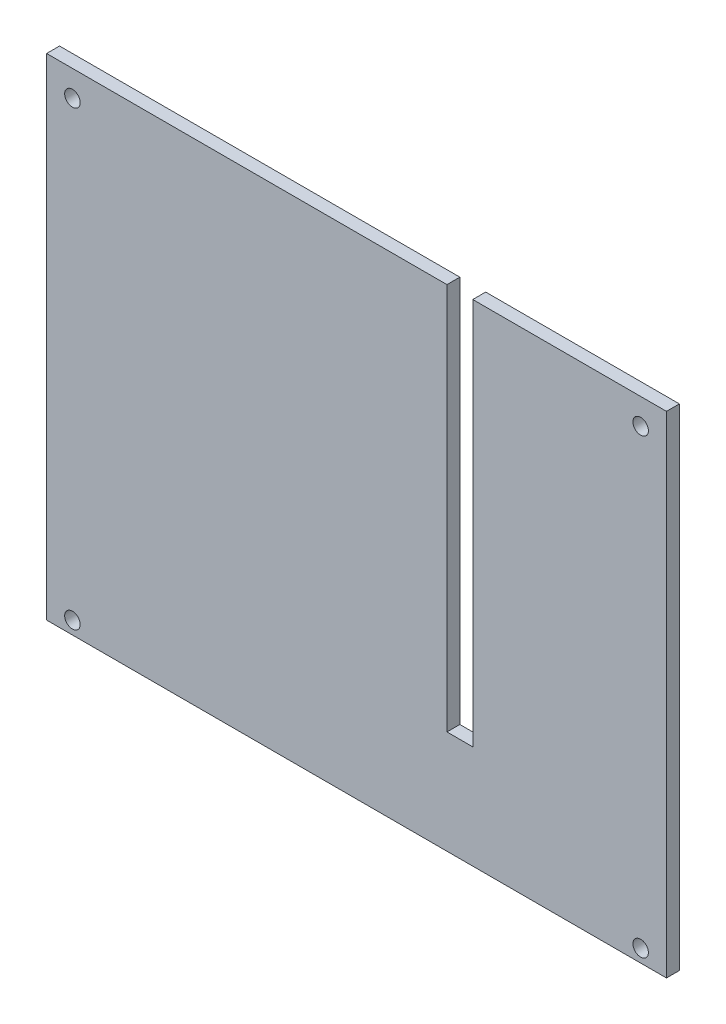
SolidWorks part; units mm, degrees
ref_plane "Plan de face" through (0, 0, 0) normal (0, 0, 1) x (1, 0, 0)
ref_plane "Plan de dessus" through (0, 0, 0) normal (0, 1, 0) x (1, 0, 0)
ref_plane "Plan de droite" through (0, 0, 0) normal (1, 0, 0) x (0, 0, -1)
sketch "Esquisse1" plane through (0, 0, 0) normal (0, 0, 1) x (1, 0, 0)
  line L1 (0, 0) -> (240, 0)
  line L2 (0, 0) -> (0, -190)
  line L3 (0, -190) -> (240, -190)
  line L4 (240, 0) -> (240, -190)
  dimension "D1" = 240
  dimension "D2" = 190
extrude "Boss.-Extru.1" add sketch "Esquisse1" along normal blind 5
sketch "Esquisse2" plane through (0, 0, 5) normal (0, 0, 1) x (1, 0, 0)
  line L0 (155, 0) -> (155, -150)
  line L1 (240, 0) -> (0, 0) construction
  line L2 (155, -150) -> (165, -150)
  line L3 (165, -150) -> (165, 0)
  line L4 (165, 0) -> (155, 0)
  line L5 (240, -190) -> (240, 0) construction
  dimension "D1" = 150
  dimension "D2" = 10
  dimension "D3" = 75
extrude "Enlèv. mat.-Extru.1" cut sketch "Esquisse2" against normal blind 5
sketch "Esquisse3" plane through (0, 0, 0) normal (0, 0, -1) x (-1, 0, 0)
  line L0 (-120, -190) -> (-120, 0) construction
  line L1 (0, -190) -> (-240, -190) construction
  line L2 (-155, 0) -> (0, 0) construction
  line L3 (0, 0) -> (0, -190) construction
  circle A0 centre (-10, -185) radius 3
  circle A1 centre (-10, -10) radius 3
  circle A2 centre (-230, -185) radius 3
  circle A3 centre (-230, -10) radius 3
  dimension "D1" = 6
  dimension "D2" = 6
  dimension "D3" = 10
  dimension "D4" = 10
  dimension "D5" = 10
  dimension "D6" = 5
extrude "Enlèv. mat.-Extru.2" cut sketch "Esquisse3" against normal blind 10
